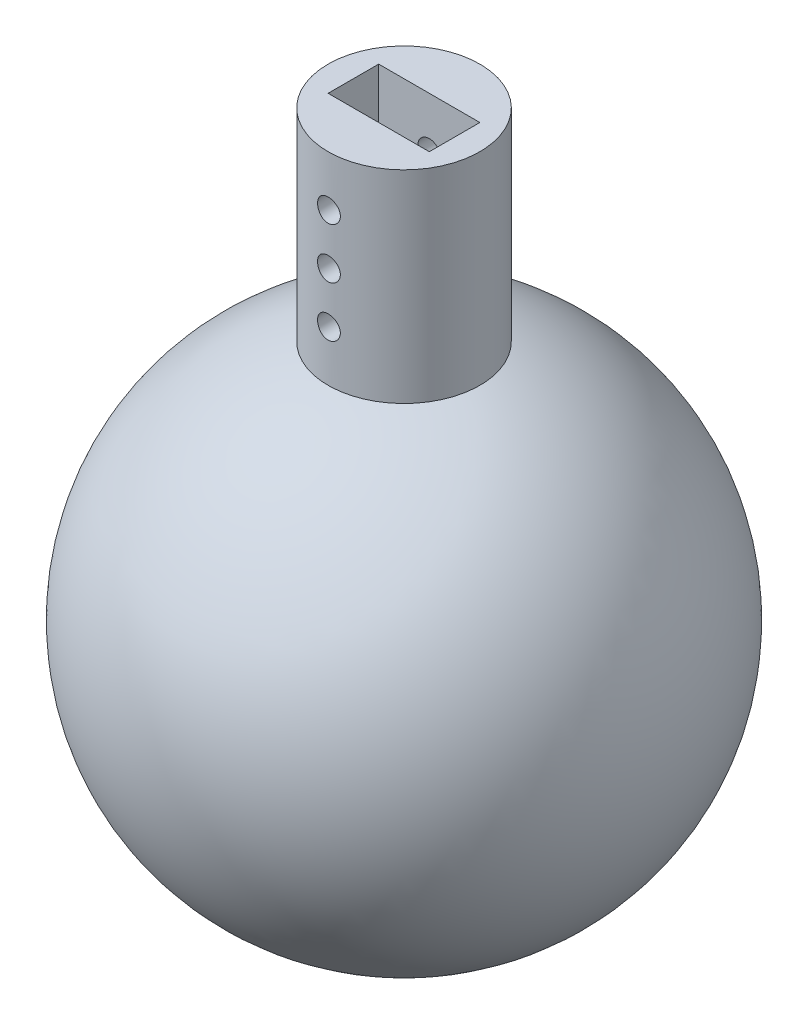
SolidWorks part; units mm, degrees
material "Rubber"
ref_plane "Front Plane" through (0, 0, 0) normal (0, 0, 1) x (1, 0, 0)
ref_plane "Top Plane" through (0, 0, 0) normal (0, 1, 0) x (1, 0, 0)
ref_plane "Right Plane" through (0, 0, 0) normal (1, 0, 0) x (0, 0, -1)
sketch "Sketch1" plane through (0, 0, 0) normal (0, 0, 1) x (1, 0, 0)
  line L0 (0, 0) -> (0, 40)
  line L1 (0, 40) -> (15, 40)
  line L2 (15, 40) -> (15, -47.697)
  line L3 (15, -47.697) -> (15, -97.697)
  arc A0 (0, 0) -> (15, -97.697) centre (15, -47.697) ccw
  dimension "D3" = 50
  dimension "D1" = 40
  dimension "D2" = 15
revolve "Revolve1" add sketch "Sketch1" angle 360 about L2
sketch "Sketch2" plane through (0, 0, 0) normal (0, 0, 1) x (1, 0, 0)
  line L0 (30, 40) -> (0, 40) construction
  line L1 (30, 0) -> (30, 40) construction
  circle A0 centre (15, 30) radius 2.25
  circle A1 centre (15, 20) radius 2.25
  circle A2 centre (15, 10) radius 2.25
  dimension "D1" = 4.5
  dimension "D2" = 10
  dimension "D3" = 15
  dimension "D4" = 3
extrude "Cut-Extrude1" cut sketch "Sketch2" against normal blind 15 and the other way blind 15
sketch "Sketch3" plane through (0, 40, 0) normal (0, 1, 0) x (1, 0, 0)
  line L1 (5, -5) -> (25, -5)
  line L2 (5, -5) -> (5, 5)
  line L3 (5, 5) -> (25, 5)
  line L4 (25, -5) -> (25, 5)
  line L5 (5, -5) -> (25, 5) construction
  line L6 (5, 5) -> (25, -5) construction
  point P0 (15, 0)
  dimension "D1" = 20
  dimension "D2" = 10
extrude "Cut-Extrude2" cut sketch "Sketch3" against normal blind 40
